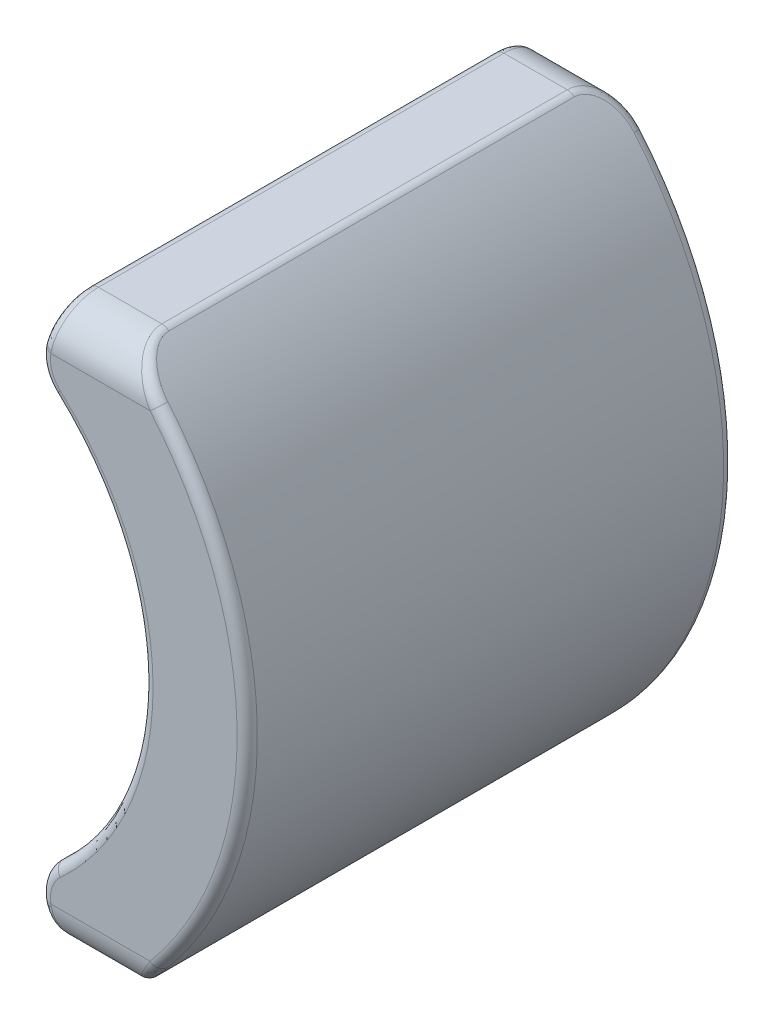
SolidWorks part; units mm, degrees
ref_plane "Front Plane" through (0, 0, 0) normal (0, 0, 1) x (1, 0, 0)
ref_plane "Top Plane" through (0, 0, 0) normal (0, 1, 0) x (1, 0, 0)
ref_plane "Right Plane" through (0, 0, 0) normal (1, 0, 0) x (0, 0, -1)
sketch "Sketch1" plane through (0, 0, 0) normal (0, 0, 1) x (1, 0, 0)
  line L0 (0, 0) -> (9.63, 0) construction
  line L1 (6.6218, -6.88) -> (4.7618, -6.88)
  line L2 (4.7618, -6.88) -> (4.4155, -5.38)
  line L3 (4.7618, 6.88) -> (4.4155, 5.38)
  line L4 (6.6218, 6.88) -> (4.7618, 6.88)
  arc A0 (6.6218, 6.88) -> (6.6218, -6.88) centre (0.2582, 0) cw
  arc A1 (4.4155, 5.38) -> (4.4155, -5.38) centre (0.2582, 0) cw
  point P6 (9.63, 0)
  dimension "D1" = 9.63
  dimension "D2" = 6.88
  dimension "D3" = 103
  dimension "D4" = 1.86
  dimension "D5" = 1.5
extrude "Boss-Extrude1" add sketch "Sketch1" along normal blind 12
fillet "Fillet1" radius 1 2 edges at (4.4155, -5.38, 6) (4.4155, 5.38, 6)
fillet "Fillet2" radius 1 4 edges at (5.6918, -6.88, 0) (5.6918, -6.88, 12) (5.6918, 6.88, 0) (5.6918, 6.88, 12)
fillet "Fillet3" radius 0.25 24 edges at (6.886, -6.6259, 11.6661) (6.6218, -6.88, 6) (6.7548, -6.7546, 0.5152) (9.63, 0, 0) (6.886, 6.6259, 0.3339) (6.6218, 6.88, 6) (6.7548, 6.7546, 11.4848) (4.7018, 6.6199, 11.6727) (4.7618, 6.88, 6) (4.7018, 6.6199, 0.3273) (4.5877, 5.4078, 0) (7.0573, 0, 0) (4.5877, -5.4078, 0) (4.7018, -6.6199, 0.3273) (4.7618, -6.88, 6) (4.7018, -6.6199, 11.6727) (7.0573, 0, 12) (4.5877, 5.4078, 12) (9.63, 0, 12) (4.5877, -5.4078, 12)
